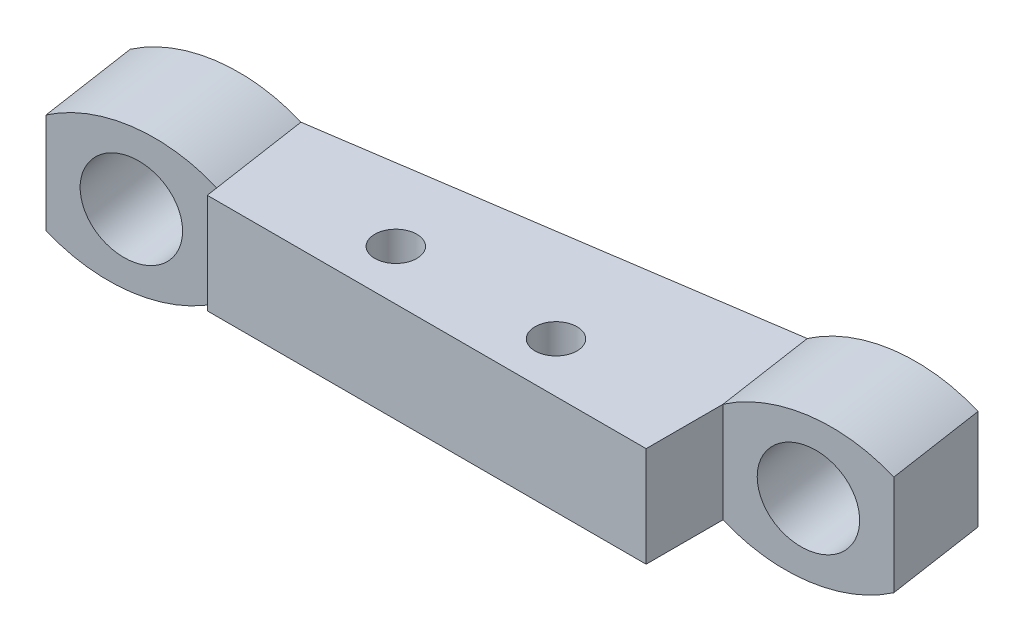
SolidWorks part; units mm, degrees
ref_plane "Front" through (0, 0, 0) normal (0, 0, 1) x (1, 0, 0)
ref_plane "Top" through (0, 0, 0) normal (0, 1, 0) x (1, 0, 0)
ref_plane "Right" through (0, 0, 0) normal (1, 0, 0) x (0, 0, -1)
sketch "草图3" plane through (0, 0, 0) normal (0, 1, 0) x (1, 0, 0)
  line L0 (-22, 0) -> (-22, 11)
  line L1 (-22, 11) -> (22, 17.5758)
  line L2 (22, 17.5758) -> (22, 0)
  line L3 (22, 0) -> (-22, 0)
  dimension "D1" = 8.5
  dimension "D2" = 11
  dimension "D3" = 44
extrude "凸台-拉伸2" add sketch "草图3" along normal mid plane 10 separate body
sketch "草图4" plane through (-2.0887, 0, -13.9758) normal (-0.1478, 0, -0.989) x (-0.989, 0, 0.1478)
  line L0 (-24.3562, -5) -> (-24.3562, 5)
  line L1 (-24.3562, 5) -> (-39.3562, 5) construction
  line L2 (-39.3562, 5) -> (-39.3562, -5)
  line L3 (-39.3562, -5) -> (-24.3562, -5) construction
  line L4 (-24.3562, 0) -> (-31.8562, 0) construction
  line L5 (-2.1119, -5) -> (-2.1119, 5) construction
  line L7 (-24.3562, -5) -> (20.1324, -5) construction
  line L8 (-24.3562, 5) -> (20.1324, 5) construction
  line L9 (20.1324, 0) -> (27.6324, 0) construction
  line L10 (35.1324, -5) -> (20.1324, -5) construction
  line L11 (20.1324, 5) -> (35.1324, 5) construction
  line L12 (35.1324, 5) -> (35.1324, -5)
  line L13 (20.1324, -5) -> (20.1324, 5)
  circle A0 centre (-31.8562, 0) radius 4.5
  arc A1 (-24.3562, -5) -> (-39.3562, -5) centre (-31.8562, 6.8216) cw
  arc A2 (-24.3562, 5) -> (-39.3562, 5) centre (-31.8562, -6.8216) ccw
  arc A3 (20.1324, 5) -> (35.1324, 5) centre (27.6324, -6.8216) cw
  arc A4 (20.1324, -5) -> (35.1324, -5) centre (27.6324, 6.8216) ccw
  circle A5 centre (27.6324, 0) radius 4.5
  dimension "D1" = 9
  dimension "D4" = 14
  dimension "D5" = 14
  dimension "D2" = 7.5
  dimension "D3" = 15
extrude "凸台-拉伸3" add sketch "草图4" against normal blind 10
sketch "草图5" plane through (0, 0, 0) normal (0, 1, 0) x (1, 0, 0)
  line L0 (23.4781, 7.6857) -> (22, 7.4648)
  line L1 (22, 0) -> (22, 17.5758) construction
  line L2 (22, 7.4648) -> (22, 17.5758)
  line L3 (22, 17.5758) -> (23.4781, 7.6857)
extrude "凸台-拉伸4" add sketch "草图5" along normal mid plane 10
sketch "草图6" plane through (0, 0, 0) normal (0, 1, 0) x (1, 0, 0)
  line L0 (-22, 0) -> (-22, 0.8889)
  line L1 (-22, 0.8889) -> (-20.5219, 1.1098)
  line L2 (-20.5219, 1.1098) -> (-20.356, 0)
  line L3 (-22, 0) -> (22, 0) construction
  line L4 (-20.356, 0) -> (-22, 0)
extrude "切除-拉伸1" cut sketch "草图6" against normal mid plane 10
sketch "草图7" plane through (0, 0, 0) normal (0, 1, 0) x (1, 0, 0)
  line L0 (22, 0) -> (24.6267, 0)
  line L1 (24.6267, 0) -> (23.4781, 7.6857)
  line L2 (23.4781, 7.6857) -> (22, 7.4648)
  line L3 (22, 7.4648) -> (22, 0)
  line L4 (23.4781, 7.6857) -> (22, 17.5758) construction
extrude "凸台-拉伸5" add sketch "草图7" along normal mid plane 10
sketch "草图8" plane through (0, 0, 0) normal (0, 1, 0) x (1, 0, 0)
  line L0 (23.4781, 0) -> (23.4781, 7.6857)
  line L1 (-20.356, 0) -> (24.6267, 0) construction
  line L2 (23.4781, 7.6857) -> (24.6267, 0)
  line L3 (24.6267, 0) -> (23.4781, 0)
  dimension "D1" = 8.5
extrude "切除-拉伸2" cut sketch "草图8" against normal mid plane 10
sketch "草图9" plane through (0, 0, 0) normal (0, 1, 0) x (1, 0, 0)
  line L0 (23.4781, 5) -> (9.4781, 5) construction
  line L1 (23.4781, 7.6857) -> (23.4781, 0) construction
  line L2 (9.4781, 5) -> (-6.5219, 5) construction
  line L3 (-20.356, 0) -> (23.4781, 0) construction
  circle A0 centre (9.4781, 5) radius 2.1
  circle A1 centre (-6.5219, 5) radius 2.1
  dimension "D1" = 4.2
  dimension "D2" = 14
  dimension "D3" = 16
  dimension "D4" = 5
extrude "切除-拉伸3" cut sketch "草图9" against normal mid plane 10
